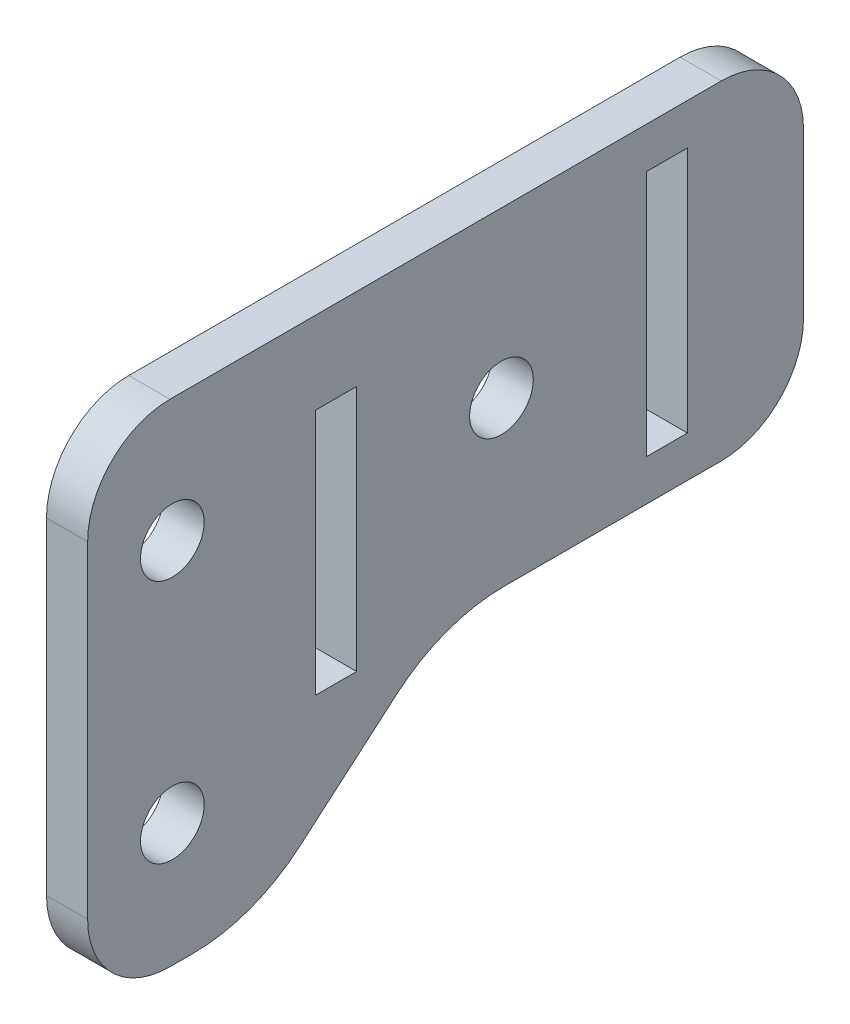
SolidWorks part; units mm, degrees
material "AISI 4340 Steel, annealed"
ref_plane "X-Y Datum" through (0, 0, 0) normal (0, 0, 1) x (1, 0, 0)
ref_plane "X-Z Datum" through (0, 0, 0) normal (0, 1, 0) x (1, 0, 0)
ref_plane "Y-Z Datum" through (0, 0, 0) normal (1, 0, 0) x (0, 0, -1)
sketch "Sketch1" plane through (0, 0, 0) normal (1, 0, 0) x (0, 0, -1)
  line L0 (23.3101, -8.1843) -> (23.3101, 17.2157) construction
  line L1 (-31.9349, 17.2157) -> (23.3101, 17.2157)
  line L2 (-31.9349, 17.2157) -> (-31.9349, -20.7167)
  line L5 (23.3101, -8.1843) -> (0.1935, -8.1843) construction
  line L6 (-8.0768, -11.2463) -> (-15.5452, -17.6547) construction
  line L7 (-23.8155, -20.7167) -> (-43.8887, -20.7167) construction
  line L8 (23.3101, -8.1843) -> (23.3101, 17.2157)
  line L9 (23.3101, -8.1843) -> (0.1935, -8.1843)
  line L10 (-8.0768, -11.2463) -> (-15.5452, -17.6547)
  line L11 (-23.8155, -20.7167) -> (-31.9349, -20.7167)
  arc A6 (0.1935, -8.1843) -> (-8.0768, -11.2463) centre (0.1935, -20.8843) ccw construction
  arc A7 (-23.8155, -20.7167) -> (-15.5452, -17.6547) centre (-23.8155, -8.0167) ccw construction
  arc A8 (0.1935, -8.1843) -> (-8.0768, -11.2463) centre (0.1935, -20.8843) ccw
  arc A9 (-23.8155, -20.7167) -> (-15.5452, -17.6547) centre (-23.8155, -8.0167) ccw
  point P0 (0, 0)
  dimension "D2" = 55.245
extrude "Boss-Extrude1" add sketch "Sketch1" along normal blind 3.175
sketch "Sketch7" plane through (0, 0, 0) normal (-1, 0, 0) x (0, 0, 1)
  line L0 (-11.176, 14.0407) -> (-14.351, 14.0407)
  line L1 (-11.176, 14.0407) -> (-11.176, -5.0093)
  line L2 (-11.176, -5.0093) -> (-14.351, -5.0093)
  line L3 (-14.351, -5.0093) -> (-14.351, 14.0407)
  line L4 (14.351, 10.8657) -> (11.176, 10.8657)
  line L5 (11.176, 10.8657) -> (11.176, -8.1843)
  line L6 (11.176, -8.1843) -> (14.351, -8.1843)
  line L7 (14.351, -8.1843) -> (14.351, 10.8657)
  line L8 (-23.3101, 17.2157) -> (31.9349, 17.2157) construction
  line L9 (-23.3101, 17.2157) -> (31.9349, 17.2157) construction
  point P12 (14.351, 1.3407)
  dimension "D1" = 3.175
  dimension "D2" = 19.05
  dimension "D3" = 15.875
  dimension "D4" = 22.352
  dimension "D5" = 19.05
  dimension "D6" = 3.175
  dimension "D7" = 3.175
  dimension "D8" = 11.176
  dimension "D9" = 3.175
extrude "Cut-Extrude1" cut sketch "Sketch7" against normal blind 3.175
sketch "Sketch4" plane through (0, 0, 0) normal (-1, 0, 0) x (0, 0, 1)
  point P0 (19.05, 4.7625)
  point P1 (-15.875, -5.3975)
  point P2 (19.05, -15.5575)
  dimension "D1" = 20.32
  dimension "D2" = 15.5575
  dimension "D3" = 19.05
  dimension "D4" = 15.875
  dimension "D5" = 10.16
hole_wizard "#10 (0.1935) Diameter Hole1" positions "Sketch5" profile "Sketch6" hole size "#10" standard "ANSI Inch"
sketch "Sketch5" plane through (0, 0, 0) normal (-1, 0, 0) x (0, 0, 1)
  line L0 (-23.3101, 17.2157) -> (31.9349, 17.2157) construction
  line L1 (31.9349, -20.7167) -> (23.8155, -20.7167) construction
  line L2 (14.351, -8.1843) -> (14.351, 10.8657) construction
  point P0 (25.4, 7.6907)
  point P3 (25.4, -11.1917)
  point P6 (0, 4.5157)
  dimension "D1" = 12.7
  dimension "D2" = 9.525
  dimension "D3" = 9.525
  dimension "D4" = 11.049
sketch "Sketch6" plane through (0, 7.6907, 25.4) normal (0, 1, 0) x (0, 0, 1)
  line L0 (0, 0) -> (0, 11.176)
  line L1 (0, 11.176) -> (2.4574, 9.6994)
  line L2 (2.4574, 9.6994) -> (2.4574, 0)
  line L5 (2.4574, 0) -> (0, 0)
  line L10 (0, 11.176) -> (-2.4575, 9.6994) construction
  line L11 (0, -6.35) -> (0, 107.95) construction
  dimension "Hole Dia." = 4.9149
  dimension "Hole Depth" = 11.176
  dimension "Drill Angle" = 118
fillet "Fillet1" radius 6.35 4 edges at (1.5875, 17.2157, 31.9349) (1.5875, 17.2157, -23.3101) (1.5875, -8.1843, -23.3101) (1.5875, -20.7167, 31.9349)
